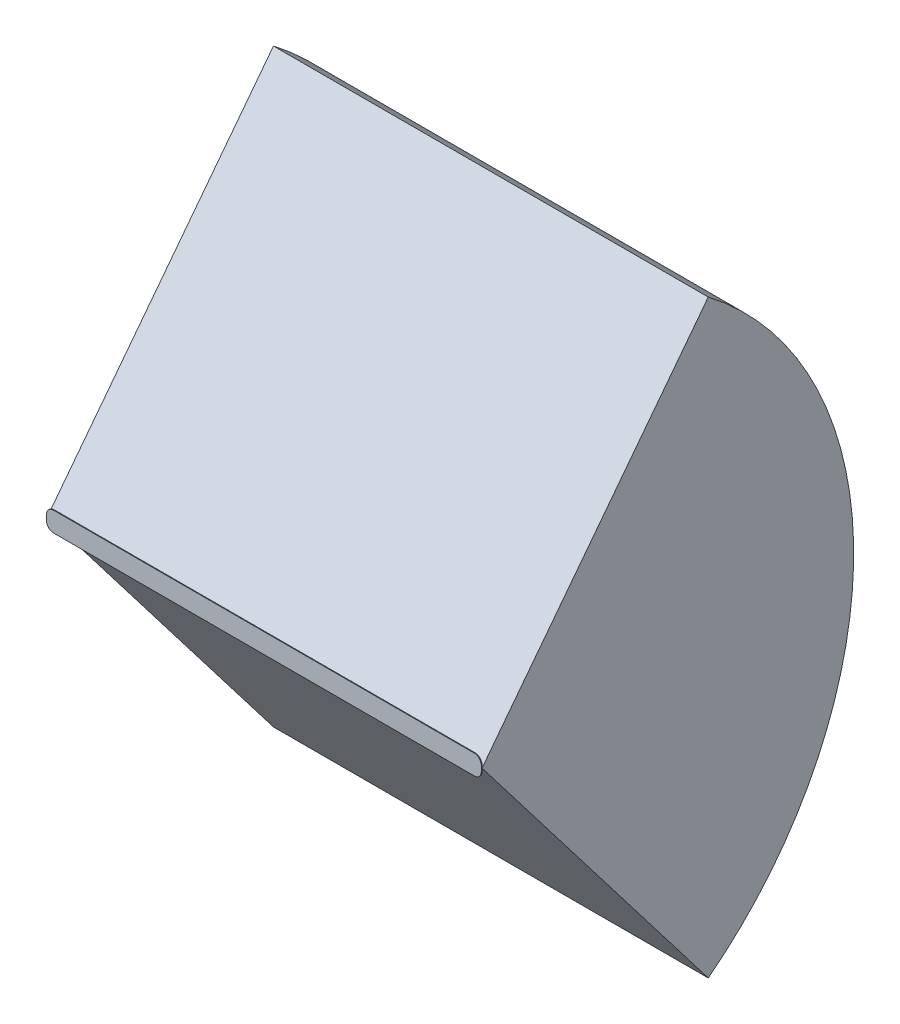
SolidWorks part; units mm, degrees
ref_plane "Plan de face" through (0, 0, 0) normal (0, 0, 1) x (1, 0, 0)
ref_plane "Plan de dessus" through (0, 0, 0) normal (0, 1, 0) x (1, 0, 0)
ref_plane "Plan de droite" through (0, 0, 0) normal (1, 0, 0) x (0, 0, -1)
sketch "Esquisse1" plane through (0, 0, 0) normal (0, 0, 1) x (1, 0, 0)
  line L1 (-298, -14) -> (298, -14)
  line L2 (-308, -4) -> (-308, 4)
  line L3 (-298, 14) -> (298, 14)
  line L4 (308, -4) -> (308, 4)
  line L5 (-308, -14) -> (308, 14) construction
  line L6 (-308, 14) -> (308, -14) construction
  arc A0 (-298, -14) -> (-308, -4) centre (-298, -4) cw
  arc A1 (-308, 4) -> (-298, 14) centre (-298, 4) cw
  arc A2 (298, -14) -> (308, -4) centre (298, -4) ccw
  arc A3 (308, 4) -> (298, 14) centre (298, 4) ccw
  point P0 (0, 0)
  dimension "D3" = 10
  dimension "D1" = 616
  dimension "D2" = 28
extrude "Boss.-Extru.1" add sketch "Esquisse1" along normal blind 1
sketch "Esquisse3" plane through (308, 0, 0) normal (1, 0, 0) x (0, 0, -1)
  line L0 (0, 0) -> (-617.9558, 0) construction
  line L1 (0, -4) -> (0, 4) construction
  line L2 (0, 0) -> (320.5442, 417.7414)
  line L3 (0, 0) -> (320.5442, -417.7414)
  line L4 (0, 0) -> (351.8183, 0) construction
  arc A0 (320.5442, -417.7414) -> (320.5442, 417.7414) centre (0, 0) ccw
  dimension "D1" = 105
  dimension "D2" = 52.5
extrude "Boss.-Extru.2" add sketch "Esquisse3" against normal through all separate body
